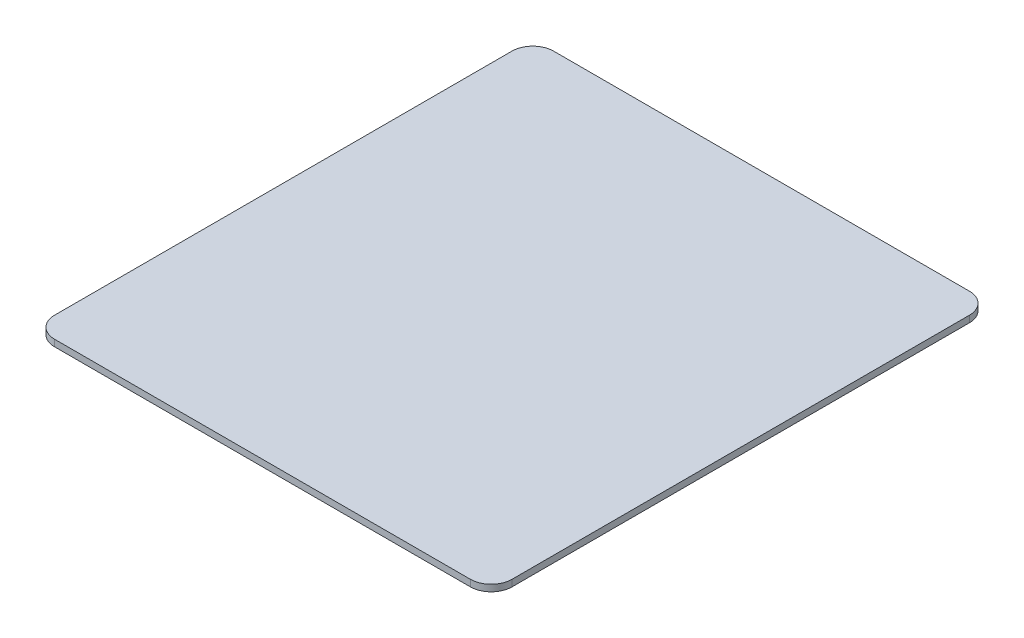
SolidWorks part; units mm, degrees
ref_plane "Front Plane" through (0, 0, 0) normal (0, 0, 1) x (1, 0, 0)
ref_plane "Top Plane" through (0, 0, 0) normal (0, 1, 0) x (1, 0, 0)
ref_plane "Right Plane" through (0, 0, 0) normal (1, 0, 0) x (0, 0, -1)
sketch "Sketch1" plane through (0, 0, 0) normal (0, 1, 0) x (1, 0, 0)
  line L1 (10, 0) -> (210, 0)
  line L2 (0, 10) -> (0, 230)
  line L3 (10, 240) -> (210, 240)
  line L4 (220, 10) -> (220, 230)
  arc A0 (210, 0) -> (220, 10) centre (210, 10) ccw
  arc A1 (10, 0) -> (0, 10) centre (10, 10) cw
  arc A2 (210, 240) -> (220, 230) centre (210, 230) cw
  arc A3 (0, 230) -> (10, 240) centre (10, 230) cw
  point P9 (0, 0)
  point P12 (220, 240)
  point P15 (0, 240)
  dimension "D3" = 10
  dimension "D1" = 220
  dimension "D2" = 240
extrude "Boss-Extrude1" add sketch "Sketch1" along normal blind 3.175
